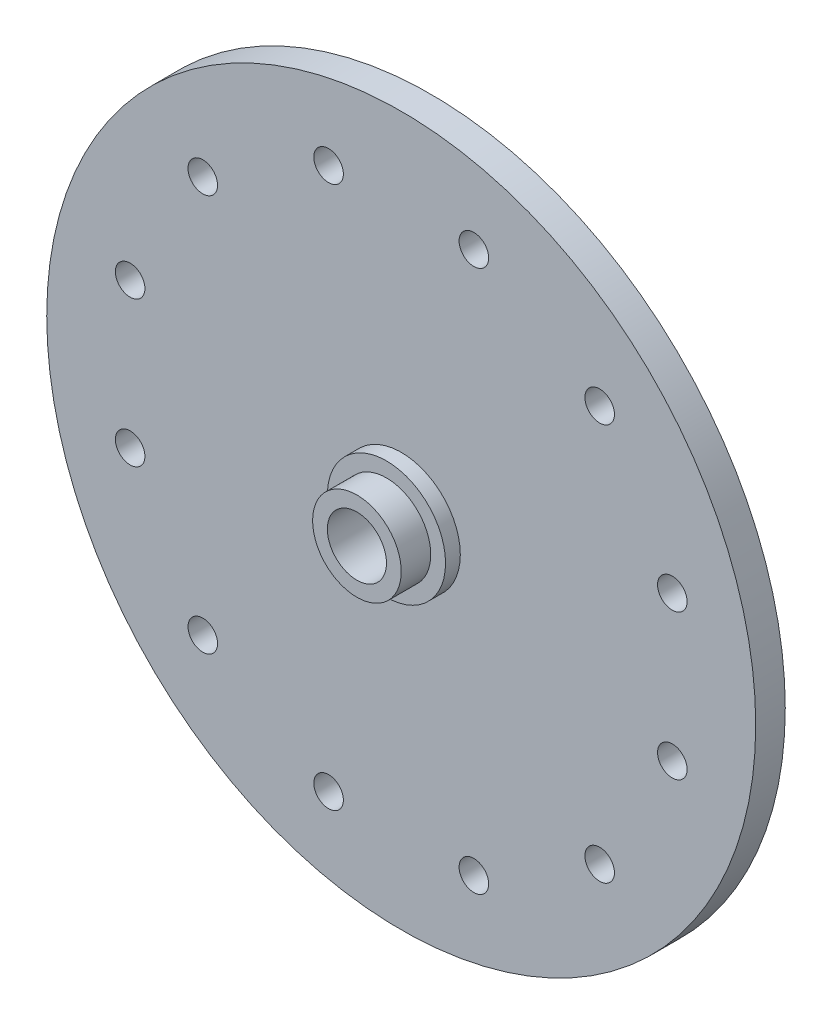
SolidWorks part; units mm, degrees
ref_plane "Front Plane" through (0, 0, 0) normal (0, 0, 1) x (1, 0, 0)
ref_plane "Top Plane" through (0, 0, 0) normal (0, 1, 0) x (1, 0, 0)
ref_plane "Right Plane" through (0, 0, 0) normal (1, 0, 0) x (0, 0, -1)
sketch "Sketch2" plane through (0, 0, 0) normal (0, 0, 1) x (1, 0, 0)
  circle A0 centre (0, 0) radius 12.7
  circle A1 centre (0, 0) radius 152.4
extrude "Boss-Extrude1" add sketch "Sketch2" against normal blind 12.7
sketch "Sketch3" plane through (0, 0, 0) normal (0, 0, 1) x (1, 0, 0)
  circle A0 centre (85.3124, 85.3124) radius 6.35
extrude "Cut-Extrude1" cut sketch "Sketch3" against normal through all
sketch "Sketch4" plane through (0, 0, 0) normal (0, 0, 1) x (1, 0, 0)
  circle A2 centre (0, 0) radius 120.65
  circle A3 centre (0, 0) radius 120.65
  dimension "D1" = 31.75
pattern_curve "CrvPattern1" of "Cut-Extrude1" parameters "D1"=12, "D3"=2.54, "D2"=1, "D4"=2.54
sketch "Sketch5" plane through (0, 0, 0) normal (0, 0, 1) x (1, 0, 0)
  circle A0 centre (0, 0) radius 19.05
extrude "Boss-Extrude2" add sketch "Sketch5" along normal blind 19.05
sketch "Sketch6" plane through (0, 0, 0) normal (0, 0, 1) x (1, 0, 0)
  circle A0 centre (0, 0) radius 25.4
extrude "Boss-Extrude3" add sketch "Sketch6" along normal blind 6.35
sketch "Sketch8" plane through (0, 0, -12.7) normal (0, 0, -1) x (-1, 0, 0)
  circle A0 centre (0, 0) radius 12.7
extrude "Cut-Extrude2" cut sketch "Sketch8" against normal through all
